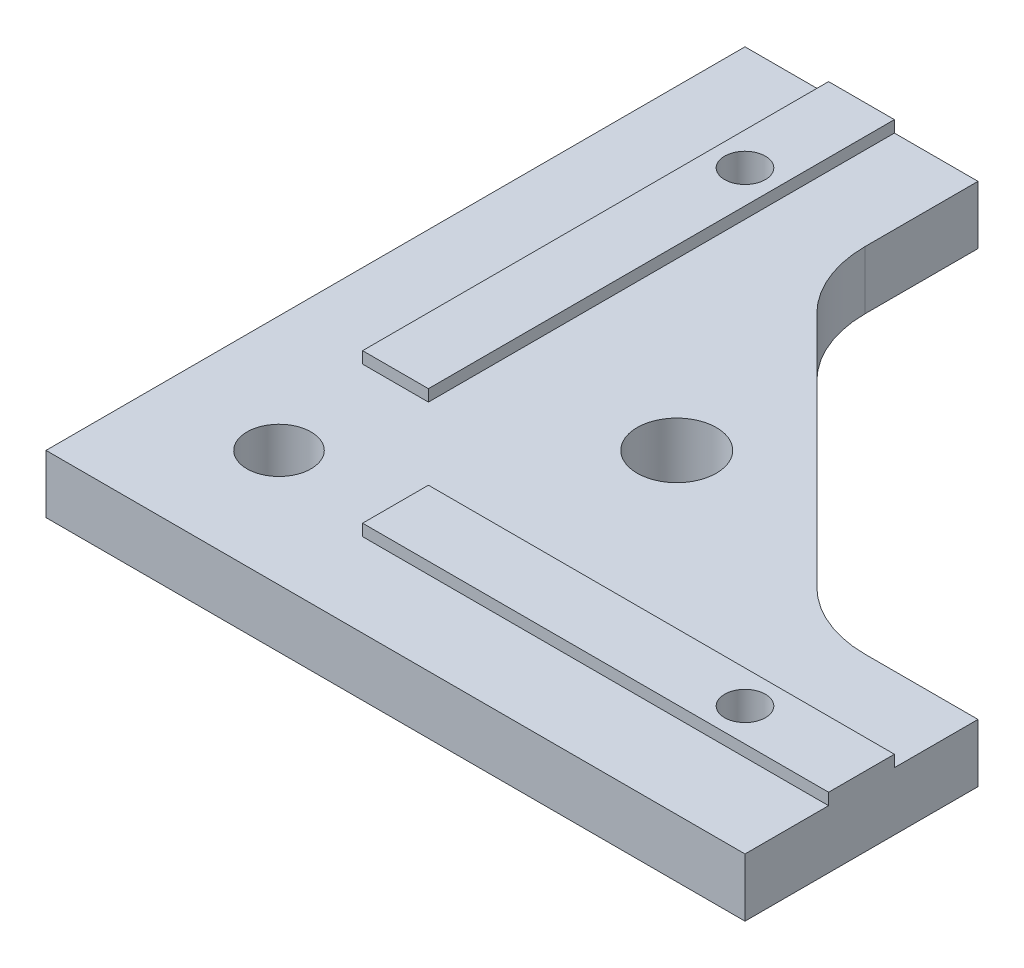
SolidWorks part; units mm, degrees
ref_plane "Plano frontal" through (0, 0, 0) normal (0, 0, 1) x (1, 0, 0)
ref_plane "Plano superior" through (0, 0, 0) normal (0, 1, 0) x (1, 0, 0)
ref_plane "Plano direito" through (0, 0, 0) normal (1, 0, 0) x (0, 0, -1)
sketch "Esboço1" plane through (0, 0, 0) normal (0, 1, 0) x (1, 0, 0)
  line L0 (0, 0) -> (0, 60)
  line L1 (0, 60) -> (20, 60)
  line L2 (20, 60) -> (60, 20)
  line L3 (60, 20) -> (60, 0)
  line L4 (60, 0) -> (0, 0)
  line L5 (10, 60) -> (10, 0) construction
  line L6 (60, 10) -> (0, 10) construction
  line L7 (52.9289, 20) -> (20, 52.9289)
  line L8 (20, 52.9289) -> (20, 20)
  line L9 (20, 20) -> (52.9289, 20)
  line L10 (20, 52.9289) -> (20, 60)
  line L11 (52.9289, 20) -> (60, 20)
  circle A0 centre (10, 50) radius 1.75
  circle A1 centre (10, 30) radius 1.75 construction
  circle A2 centre (30, 10) radius 1.75 construction
  circle A3 centre (50, 10) radius 1.75
  circle A4 centre (10, 10) radius 2.75
  dimension "D5" = 3.5
  dimension "D12" = 5.5
  dimension "D1" = 60
  dimension "D2" = 60
  dimension "D3" = 45
  dimension "D4" = 20
  dimension "D6" = 10
  dimension "D7" = 20
  dimension "D8" = 20
  dimension "D9" = 10
  dimension "D10" = 5
  dimension "D11" = 20
extrude "Ressalto-extrusão1" add sketch "Esboço1" along normal blind 5 contours L11 L9 L8 L10 L1 L0 L4 L3 A4 A3 A0
sketch "Esboço2" plane through (0, 5, 0) normal (0, 1, 0) x (1, 0, 0)
  line L0 (30, 10) -> (50, 10) construction
  line L2 (20, 12.825) -> (60, 12.825)
  line L3 (20, 12.825) -> (20, 7.175)
  line L4 (20, 7.175) -> (60, 7.175)
  line L5 (60, 12.825) -> (60, 7.175)
  line L6 (20, 12.825) -> (60, 7.175) construction
  line L7 (20, 7.175) -> (60, 12.825) construction
  line L8 (10, 50) -> (10, 30) construction
  line L10 (7.175, 60) -> (12.825, 60)
  line L11 (7.175, 60) -> (7.175, 20)
  line L12 (7.175, 20) -> (12.825, 20)
  line L13 (12.825, 60) -> (12.825, 20)
  line L14 (7.175, 60) -> (12.825, 20) construction
  line L15 (7.175, 20) -> (12.825, 60) construction
  line L16 (60, 20) -> (60, 0) construction
  line L17 (0, 60) -> (20, 60) construction
  circle A4 centre (10, 50) radius 1.75 construction
  circle A5 centre (10, 50) radius 1.75
  circle A6 centre (50, 10) radius 1.75 construction
  circle A7 centre (50, 10) radius 1.75
  point P4 (40, 10)
  point P15 (10, 40)
  dimension "D1" = 5.65
  dimension "D2" = 5.65
  dimension "D3" = 20
extrude "Ressalto-extrusão2" add sketch "Esboço2" along normal blind 1
sketch "Esboço3" plane through (0, 0, 0) normal (0, -1, 0) x (1, 0, 0)
  line L0 (0, 0) -> (33.0815, -33.0815) construction
  line L2 (20, -46.163) -> (46.163, -20)
  line L5 (20, -46.163) -> (20, -20)
  line L6 (20, -20) -> (46.163, -20)
  line L8 (20, -20) -> (60, -20) construction
  line L9 (20, -60) -> (20, -20) construction
  circle A2 centre (27.0711, -27.0711) radius 3.4
  point P3 (33.0815, -33.0815)
  point P4 (0, 0)
  point P9 (20, -46.163)
  point P11 (46.163, -20)
  point P13 (0, 0)
  point P15 (0, 0)
  point P17 (0, 0)
  point P19 (0, 0)
  point P20 (0, 0)
  line M22 (20, -20) -> (60, -20)
  line M27 (20, -60) -> (20, -20)
  dimension "D1" = 6.8
  dimension "D2" = 10
  dimension "D3" = 8.5
extrude "Ressalto-extrusão3" add sketch "Esboço3" against normal up to surface (5 mm away) contours L0 L2 A2 M27 | L0 A2 L2 M22 up to face at (10, 5, -7.25)
fillet "Filete1" radius 10 2 edges at (46.163, 2.5, -20) (20, 2.5, -46.163)
